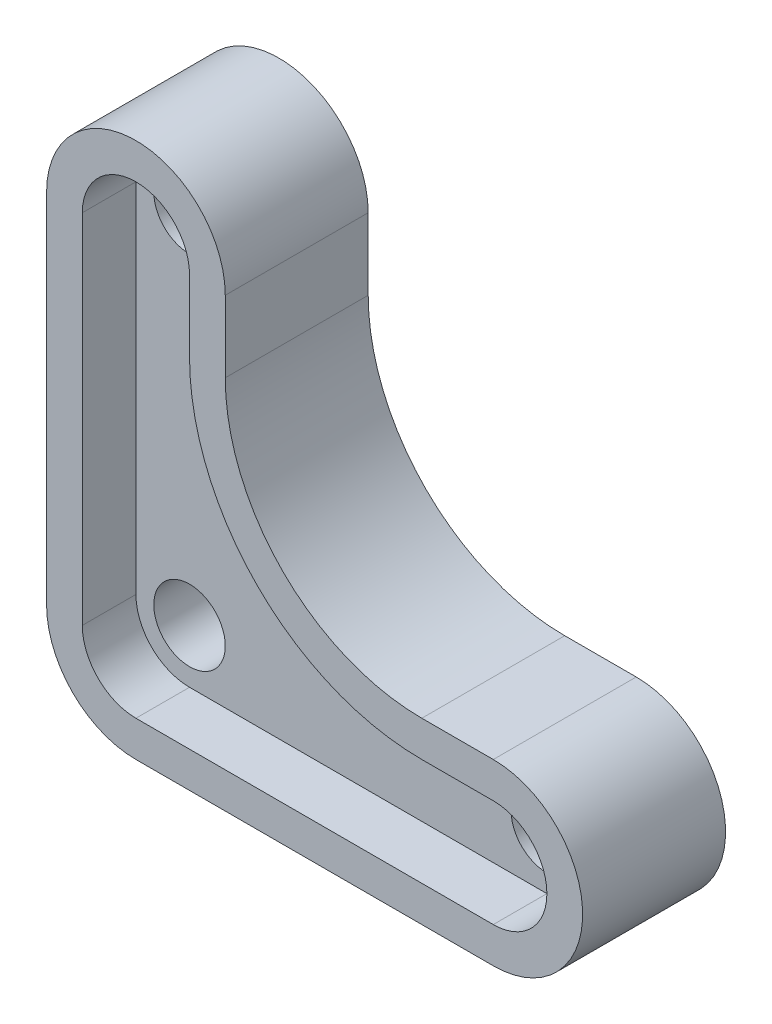
SolidWorks part; units mm, degrees
ref_plane "Front Plane" through (0, 0, 0) normal (0, 0, 1) x (1, 0, 0)
ref_plane "Top Plane" through (0, 0, 0) normal (0, 1, 0) x (1, 0, 0)
ref_plane "Right Plane" through (0, 0, 0) normal (1, 0, 0) x (0, 0, -1)
ref_plane "Plane1" through (0, 0, 13) normal (0, 0, 1) x (1, 0, 0)
sketch "Sketch1" plane through (0, 0, 13) normal (0, 0, 1) x (1, 0, 0)
  line L0 (-15, 5) -> (-15, 20)
  line L1 (-25, 20) -> (-25, -5)
  line L2 (-25, -5) -> (0, -5)
  line L3 (0, 5) -> (-15, 5)
  arc A0 (-15, 20) -> (-25, 20) centre (-20, 20) ccw
  arc A1 (0, -5) -> (0, 5) centre (0, 0) ccw
extrude "Boss-Extrude1" add sketch "Sketch1" against normal blind 8
sketch "Sketch2" plane through (0, 0, 13) normal (0, 0, 1) x (1, 0, 0)
  line L0 (-23, 20) -> (-23, -3)
  line L1 (-23, -3) -> (0, -3)
  line L2 (0, 3) -> (-17, 3)
  line L3 (-17, 3) -> (-17, 20)
  arc A0 (0, -3) -> (0, 3) centre (0, 0) ccw
  arc A1 (-17, 20) -> (-23, 20) centre (-20, 20) ccw
extrude "Cut-Extrude1" cut sketch "Sketch2" against normal blind 3
hole_wizard "Ø4.0 (4) Diameter Hole1" positions "Sketch4" profile "Sketch3" hole size "Ø4.0" standard "ANSI Metric"
sketch "Sketch4" plane through (0, 0, 5) normal (0, 0, -1) x (-1, 0, 0)
  point P0 (20, 20)
  point P1 (20, 0)
  point P2 (0, 0)
sketch "Sketch3" plane through (-20, 20, 5) normal (1, 0, 0) x (0, 1, 0)
  line L0 (0, 0) -> (0, 8)
  line L1 (0, 8) -> (2, 8)
  line L2 (2, 8) -> (2, 0)
  line L5 (2, 0) -> (0, 0)
  line L11 (0, -6.35) -> (0, 107.95) construction
  dimension "Thru Hole Dia." = 4
  dimension "Thru Hole Depth" = 8
fillet "Fillet1" radius 3 1 edges at (-23, -3, 11.5)
fillet "Fillet2" radius 5 1 edges at (-25, -5, 9)
fillet "Fillet3" radius 11 1 edges at (-15, 5, 9)
fillet "Fillet4" radius 13 1 edges at (-17, 3, 11.5)
